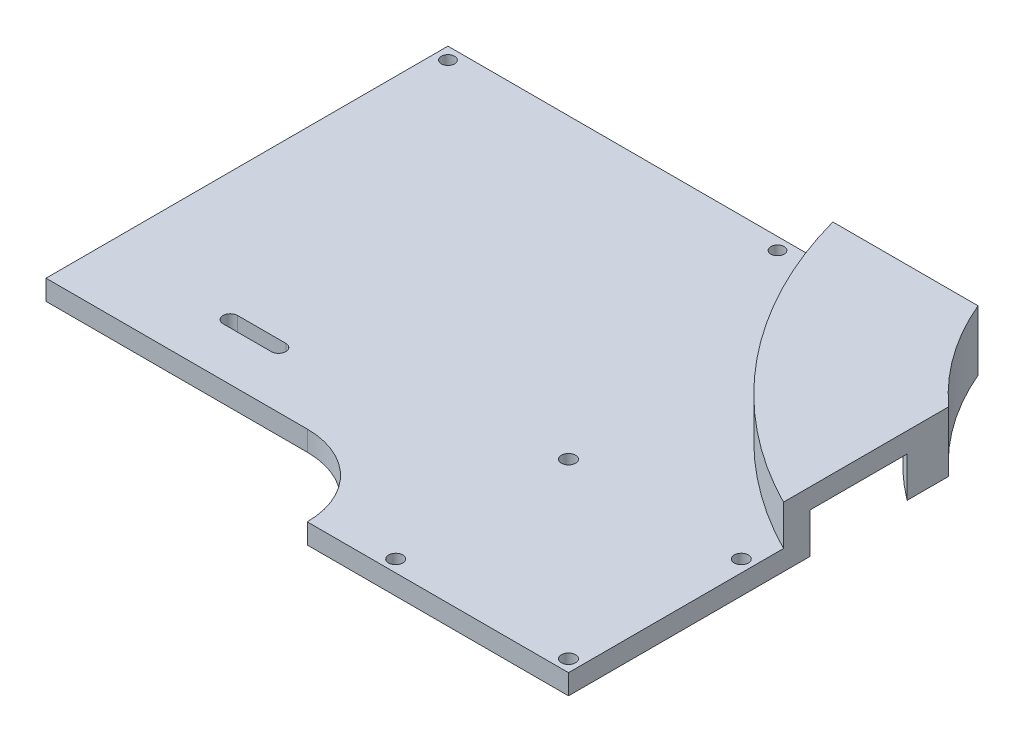
SolidWorks part; units mm, degrees
ref_plane "前视基准面" through (0, 0, 0) normal (0, 0, 1) x (1, 0, 0)
ref_plane "上视基准面" through (0, 0, 0) normal (0, 1, 0) x (1, 0, 0)
ref_plane "右视基准面" through (0, 0, 0) normal (1, 0, 0) x (0, 0, -1)
sketch "草图2" plane through (0, 0, 0) normal (0, 1, 0) x (1, 0, 0)
  line L1 (-75, -60) -> (75, -60)
  line L2 (-75, -60) -> (-75, 60)
  line L3 (-75, 60) -> (75, 60)
  line L4 (75, -60) -> (75, 60)
  line L5 (-75, -60) -> (75, 60) construction
  line L6 (-75, 60) -> (75, -60) construction
  point P0 (0, 0)
  dimension "D1" = 150
  dimension "D2" = 120
extrude "凸台-拉伸1" add sketch "草图2" along normal blind 5
sketch "草图3" plane through (0, 5, 0) normal (0, 1, 0) x (1, 0, 0)
  line L0 (75, 60) -> (-75, 60) construction
  line L1 (-75, 60) -> (-75, -60) construction
  line L2 (-43.1384, -26) -> (-31.1384, -26) construction
  line L3 (-43.1384, -24.2) -> (-31.1384, -24.2)
  line L4 (-43.1384, -27.8) -> (-31.1384, -27.8)
  line L5 (-75, -60) -> (75, -60) construction
  line L6 (75, -60) -> (75, 60) construction
  line L7 (29, -14) -> (29, -57) construction
  line L8 (72, -14) -> (72, -57) construction
  line L9 (29, -14) -> (72, -14) construction
  circle A0 centre (-72, 57) radius 1.65
  circle A1 centre (10, 57) radius 1.65
  circle A2 centre (-37, -26) radius 1.8 construction
  arc A3 (-43.1384, -24.2) -> (-43.1384, -27.8) centre (-43.1384, -26) ccw
  arc A4 (-31.1384, -27.8) -> (-31.1384, -24.2) centre (-31.1384, -26) ccw
  circle A5 centre (72, -57) radius 1.75
  circle A6 centre (29, -57) radius 1.75
  circle A7 centre (72, -14) radius 1.75
  circle A8 centre (29, -14) radius 1.75
  point P12 (-37.1384, -26)
  dimension "D1" = 3.3
  dimension "D4" = 3.3
  dimension "D7" = 3.6
  dimension "D11" = 3.5
  dimension "D14" = 3.5
  dimension "D17" = 3.5
  dimension "D18" = 3.5
  dimension "D2" = 3
  dimension "D3" = 3
  dimension "D5" = 82
  dimension "D6" = 3
  dimension "D8" = 86
  dimension "D9" = 38
  dimension "D10" = 12
  dimension "D12" = 3
  dimension "D13" = 3
  dimension "D15" = 43
  dimension "D16" = 3
  dimension "D19" = 43
extrude "切除-拉伸1" cut sketch "草图3" against normal blind 5
sketch "草图4" plane through (0, 5, 0) normal (0, 1, 0) x (1, 0, 0)
  line L1 (75, -60) -> (75, 60) construction
  line L2 (75, 60) -> (75, -6.5093)
  line L3 (75, 60) -> (20.765, 60)
  line L4 (75, 60) -> (-75, 60) construction
  circle A0 centre (123, 88) radius 79.8
  circle A1 centre (123, 88) radius 100.2
  circle A2 centre (123, 88) radius 106
  line M11 (75, -60) -> (75, 60)
  line M12 (75, 60) -> (-75, 60)
  dimension "D1" = 159.6
  dimension "D2" = 200.4
  dimension "D5" = 212
  dimension "D3" = 28
  dimension "D4" = 48
extrude "凸台-拉伸3" add sketch "草图4" along normal blind 5 contours A0 L2 M12 | A2 A1 M12 M11
sketch "草图5" plane through (0, 10, 0) normal (0, 1, 0) x (1, 0, 0)
  line L0 (20.765, 60) -> (75, 60)
  line L1 (75, 60) -> (75, -6.5093)
  arc A0 (20.765, 60) -> (75, -6.5093) centre (123, 88) ccw construction
  arc A1 (20.765, 60) -> (75, -6.5093) centre (123, 88) ccw
extrude "凸台-拉伸4" add sketch "草图5" along normal blind 5
sketch "草图6" plane through (0, 5, 0) normal (0, 1, 0) x (1, 0, 0)
  line L2 (48.2736, 60) -> (26.7917, 60)
  line L3 (75, 0.0452) -> (75, 24.2502)
  line L4 (48.2736, 60) -> (26.7917, 60)
  line L5 (75, 0.0452) -> (75, 24.2502)
  arc A2 (26.7917, 60) -> (75, 0.0452) centre (123, 88) ccw
  arc A3 (48.2736, 60) -> (75, 24.2502) centre (123, 88) ccw
  arc A4 (26.7917, 60) -> (75, 0.0452) centre (123, 88) ccw
  arc A5 (48.2736, 60) -> (75, 24.2502) centre (123, 88) ccw
  dimension "D1" = 0
extrude "切除-拉伸2" cut sketch "草图6" against normal blind 5
sketch "草图7" plane through (0, 0, 0) normal (0, -1, 0) x (1, 0, 0)
  line L0 (55.7649, -62.807) -> (81.9234, -71.4456)
  line L1 (81.9234, -71.4456) -> (79.812, -30.6411)
  arc A0 (75, -24.2502) -> (48.2736, -60) centre (123, -88) ccw construction
  arc A1 (75, -24.2502) -> (48.2736, -60) centre (123, -88) ccw
  arc A2 (79.812, -30.6411) -> (55.7649, -62.807) centre (123, -88) ccw
  line M2 (48.2736, -60) -> (75, -60)
  line M3 (75, -60) -> (75, -24.2502)
  dimension "D1" = 8
extrude "切除-拉伸4" cut sketch "草图7" against normal blind 20 contours L1 A2 L0 M3 M2 | A2 M3 M2
sketch "草图8" plane through (0, 5, 0) normal (0, 1, 0) x (1, 0, 0)
  line L0 (-75, -60) -> (-10, -60) construction
  line L1 (-75, -60) -> (75, -60) construction
  line L2 (-75, -40) -> (-10, -40)
  line L3 (-75, -80) -> (-10, -80)
  arc A0 (-75, -40) -> (-75, -80) centre (-75, -60) ccw
  arc A1 (-10, -80) -> (-10, -40) centre (-10, -60) ccw
  point P5 (-42.5, -60)
  dimension "D2" = 20
  dimension "D1" = 65
extrude "切除-拉伸5" cut sketch "草图8" against normal blind 10
